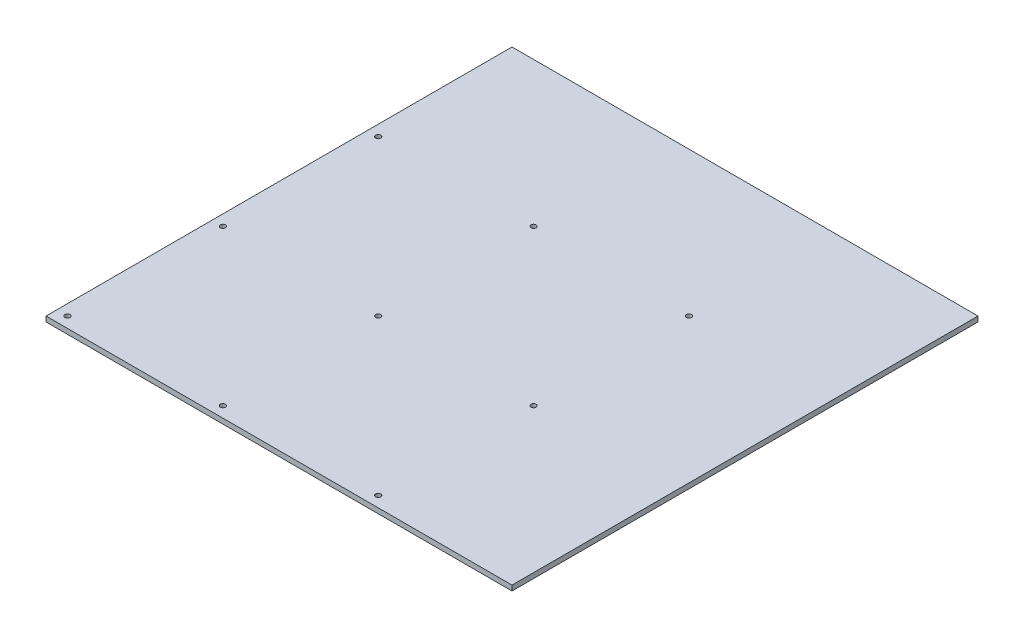
SolidWorks part; units mm, degrees
ref_plane "Front Plane" through (0, 0, 0) normal (0, 0, 1) x (1, 0, 0)
ref_plane "Top Plane" through (0, 0, 0) normal (0, 1, 0) x (1, 0, 0)
ref_plane "Right Plane" through (0, 0, 0) normal (1, 0, 0) x (0, 0, -1)
sketch "Sketch1" plane through (0, 0, 0) normal (0, 1, 0) x (1, 0, 0)
  line L0 (-257.5, -257.5) -> (-257.5, -270) construction
  line L5 (270, -270) -> (-270, -270)
  line L6 (270, -270) -> (270, 270)
  line L7 (270, 270) -> (-270, 270)
  line L8 (-270, -270) -> (-270, 270)
  line L9 (270, -270) -> (-270, 270) construction
  line L10 (270, 270) -> (-270, -270) construction
  line L11 (-257.5, -257.5) -> (-270, -257.5) construction
  circle A0 centre (-257.5, -257.5) radius 3
  circle A3 centre (-77.5, -257.5) radius 3
  circle A4 centre (102.5, -257.5) radius 3
  circle A5 centre (-77.5, -77.5) radius 3
  circle A6 centre (102.5, -77.5) radius 3
  circle A7 centre (-77.5, 102.5) radius 3
  circle A8 centre (102.5, 102.5) radius 3
  circle A9 centre (-257.5, -77.5) radius 3
  circle A10 centre (-257.5, 102.5) radius 3
  point P0 (0, 0)
  dimension "D3" = 6
  dimension "D1" = 540
  dimension "D2" = 540
  dimension "D4" = 12.5
  dimension "D5" = 12.5
  dimension "D6" = 3
  dimension "D7" = 3
extrude "Boss-Extrude1" add sketch "Sketch1" along normal blind 6
equation "\"hole\"= 6mm'UK=6, HK=7, JP=8?"
equation "\"D3@Sketch1\"=\"hole\""
